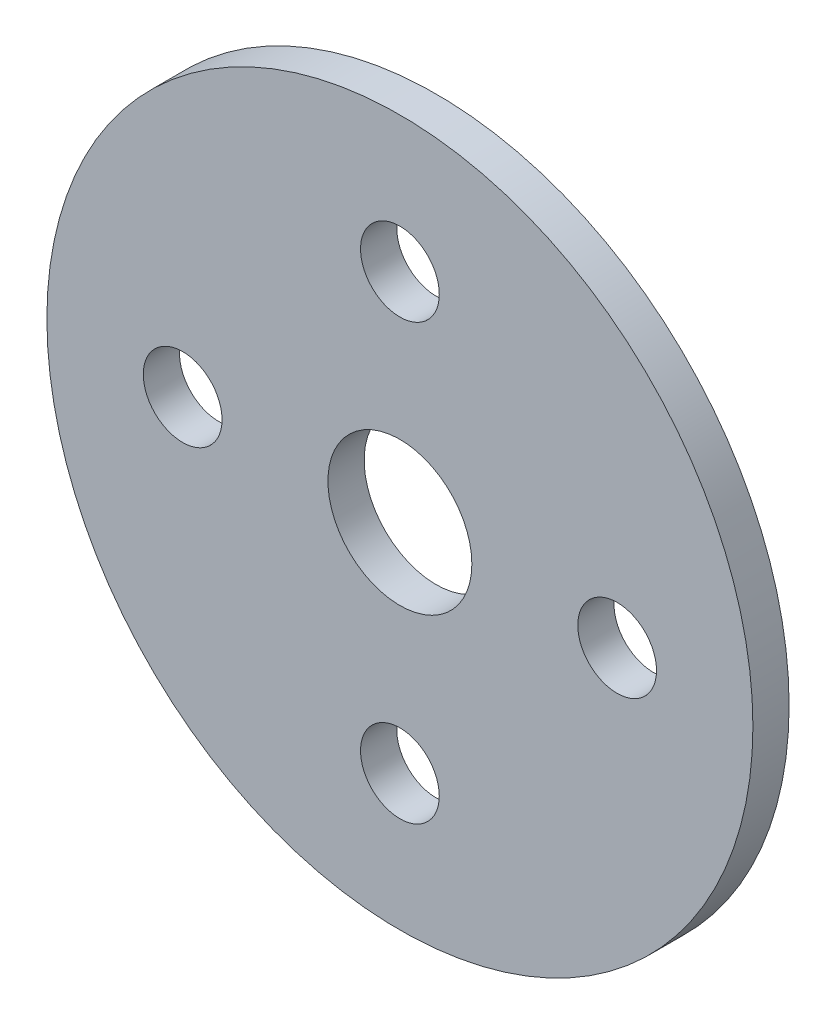
SolidWorks part; units mm, degrees
ref_plane "Front Plane" through (0, 0, 0) normal (0, 0, 1) x (1, 0, 0)
ref_plane "Top Plane" through (0, 0, 0) normal (0, 1, 0) x (1, 0, 0)
ref_plane "Right Plane" through (0, 0, 0) normal (1, 0, 0) x (0, 0, -1)
sketch "Sketch1" plane through (0, 0, 0) normal (0, 0, 1) x (1, 0, 0)
  circle A0 centre (0, 0) radius 19.5
  circle A2 centre (12, 0) radius 2.175
  circle A3 centre (0, 12) radius 2.175
  circle A4 centre (-12, 0) radius 2.175
  circle A5 centre (0, -12) radius 2.175
  circle A6 centre (0, 0) radius 3.975
  dimension "D1" = 4.35
  dimension "D2" = 4.35
  dimension "D3" = 4.35
  dimension "D4" = 4.35
  dimension "D5" = 7.95
  dimension "D6" = 39
extrude "Boss-Extrude1" add sketch "Sketch1" along normal blind 2
